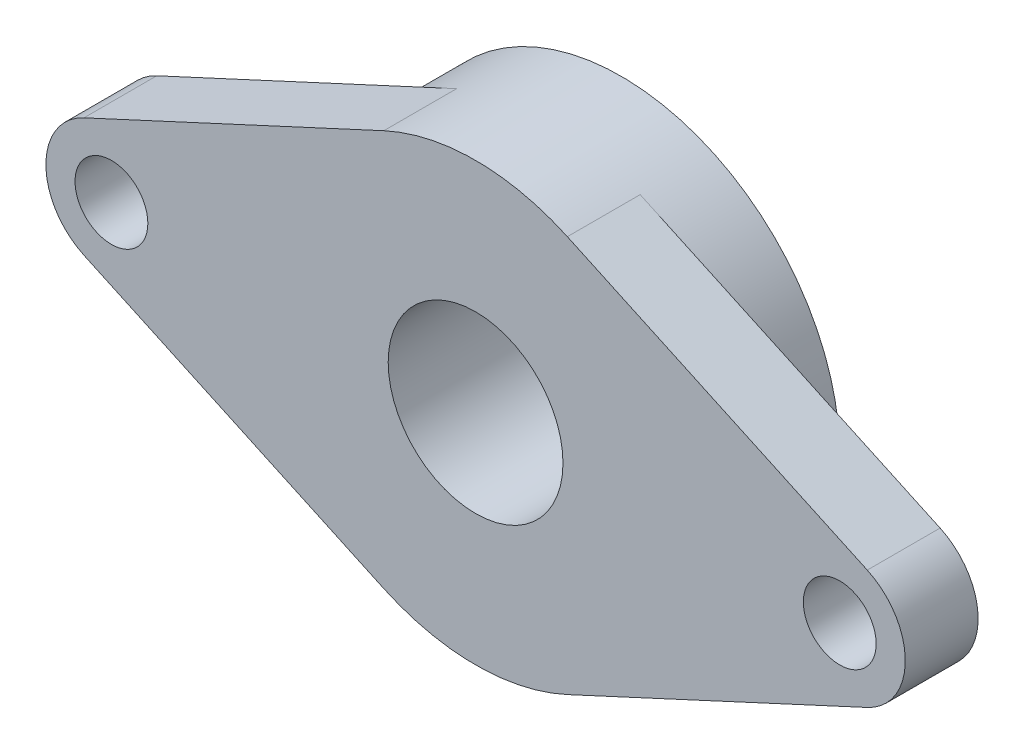
SolidWorks part; units mm, degrees
ref_plane "Front Plane" through (0, 0, 0) normal (0, 0, 1) x (1, 0, 0)
ref_plane "Top Plane" through (0, 0, 0) normal (0, 1, 0) x (1, 0, 0)
ref_plane "Right Plane" through (0, 0, 0) normal (1, 0, 0) x (0, 0, -1)
sketch "Sketch1" plane through (0, 0, 0) normal (0, 0, 1) x (1, 0, 0)
  line L0 (-27.5, 0) -> (56.6229, 0) construction
  line L1 (0, 26.1337) -> (0, -45.2983) construction
  line L2 (26.89, -4.0839) -> (6.3, -13.6129)
  line L3 (-26.89, -4.0839) -> (-6.3, -13.6129)
  line L4 (-26.89, 4.0839) -> (-6.3, 13.6129)
  line L5 (26.89, 4.0839) -> (6.3, 13.6129)
  circle A0 centre (0, 0) radius 6
  circle A1 centre (0, 0) radius 15
  circle A2 centre (-25, 0) radius 2.5
  circle A3 centre (25, 0) radius 2.5
  circle A4 centre (25, 0) radius 4.5
  circle A5 centre (-25, 0) radius 4.5
  dimension "D1" = 12
  dimension "D2" = 30
  dimension "D3" = 5
  dimension "D4" = 25
  dimension "D5" = 2
extrude "Boss-Extrude1" add sketch "Sketch1" along normal blind 5
sketch "Sketch2" plane through (0, 0, 0) normal (0, 0, -1) x (-1, 0, 0)
  circle A0 centre (0, 0) radius 15
  circle A1 centre (0, 0) radius 6
extrude "Boss-Extrude2" add sketch "Sketch2" along normal blind 5
scale "Scale1" scale about centroid uniform scaling yes scale factor 0.666667
